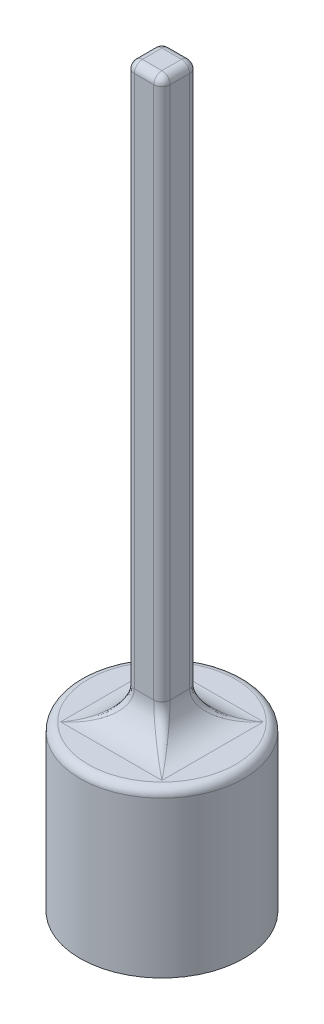
SolidWorks part; units mm, degrees
material "Plain Carbon Steel"
ref_plane "Front Plane" through (0, 0, 0) normal (0, 0, 1) x (1, 0, 0)
ref_plane "Top Plane" through (0, 0, 0) normal (0, 1, 0) x (1, 0, 0)
ref_plane "Right Plane" through (0, 0, 0) normal (1, 0, 0) x (0, 0, -1)
sketch "Sketch1" plane through (0, 0, 0) normal (0, 1, 0) x (0, 0, -1)
  circle A0 centre (0, 0) radius 6.35
  dimension "D1" = 12.7
extrude "Boss-Extrude1" add sketch "Sketch1" along normal blind 12.7 contours A0
sketch "Sketch2" plane through (-12.7, 12.7, 0) normal (0, -1, 0) x (0, 0, -1)
  line L1 (1.3891, 14.0891) -> (-1.3891, 14.0891)
  line L2 (1.3891, 14.0891) -> (1.3891, 11.3109)
  line L3 (1.3891, 11.3109) -> (-1.3891, 11.3109)
  line L4 (-1.3891, 14.0891) -> (-1.3891, 11.3109)
  line L5 (1.3891, 14.0891) -> (-1.3891, 11.3109) construction
  line L6 (1.3891, 11.3109) -> (-1.3891, 14.0891) construction
  point P0 (0, 12.7)
  dimension "D1" = 2.7781
extrude "Boss-Extrude2" add sketch "Sketch2" against normal blind 44.45 contours L1 L4 L3 L2
fillet "Fillet1" radius 2.54 4 edges at (0, 12.7, 1.3891) (-1.3891, 12.7, 0) (0, 12.7, -1.3891) (1.3891, 12.7, 0)
fillet "Fillet2" radius 0.635 13 edges at (2.133, 13.4439, 2.133) (-2.133, 13.4439, 2.133) (2.133, 13.4439, -2.133) (-2.133, 13.4439, -2.133) (1.3891, 36.195, 1.3891) (-1.3891, 36.195, 1.3891) (1.3891, 36.195, -1.3891) (-1.3891, 36.195, -1.3891) (0, 12.7, 6.35) (0, 57.15, -1.3891) (1.3891, 57.15, 0) (0, 57.15, 1.3891) (-1.3891, 57.15, 0)
hole_wizard "#10-24 Tapped Hole1" positions "Sketch4" profile "Sketch3" tap size "#10-24" standard "ANSI Inch"
sketch "Sketch4" plane through (0, 0, 0) normal (0, -1, 0) x (-1, 0, 0)
  point P0 (0, 0)
sketch "Sketch3" plane through (0, 0, 0) normal (1, 0, 0) x (0, 0, -1)
  line L0 (0, 0) -> (0, 10.6658)
  line L1 (0, 10.6658) -> (1.8986, 9.525)
  line L2 (1.8986, 9.525) -> (1.8986, 0)
  line L5 (1.8986, 0) -> (0, 0)
  line L10 (0, 10.6658) -> (-1.8987, 9.525) construction
  line L11 (0, -6.35) -> (0, 107.95) construction
  dimension "Tap Drill Dia." = 3.7973
  dimension "Tap Drill Depth" = 9.525
  dimension "Drill Angle" = 118
cosmetic thread "Hole Thread1" parameters "D1"=9.525, "D2"=4.826
